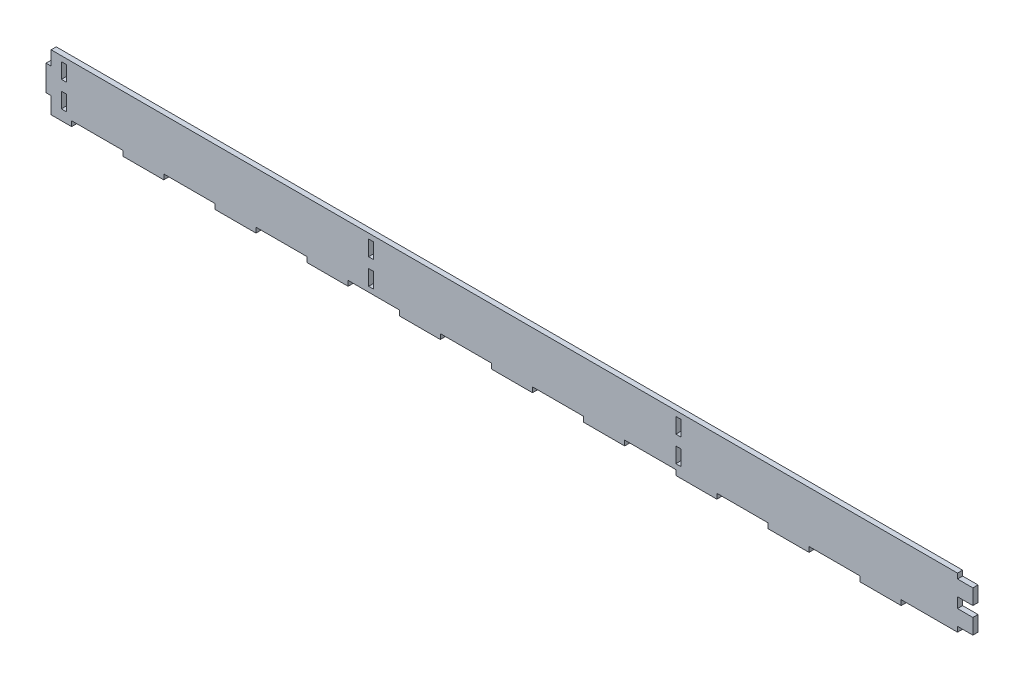
SolidWorks part; units mm, degrees
ref_plane "Front Plane" through (0, 0, 0) normal (0, 0, 1) x (1, 0, 0)
ref_plane "Top Plane" through (0, 0, 0) normal (0, 1, 0) x (1, 0, 0)
ref_plane "Right Plane" through (0, 0, 0) normal (1, 0, 0) x (0, 0, -1)
sketch "Sketch1" plane through (0, 0, 0) normal (0, 0, 1) x (1, 0, 0)
  line L0 (-15, 45) -> (-10, 45)
  line L1 (-885, 0) -> (-830, 0)
  line L2 (-885, 0) -> (-885, 5)
  line L3 (-885, 50) -> (885, 50)
  line L5 (-885, 5) -> (-900, 5)
  line L7 (-885, 20) -> (-900, 20)
  line L8 (-900, 5) -> (-900, 20)
  line L9 (-885, 45) -> (-900, 45)
  line L10 (-900, 30) -> (-900, 45)
  line L11 (-885, 30) -> (-900, 30)
  line L12 (-15, 30) -> (-15, 45)
  line L13 (-10, 30) -> (-15, 30)
  line L14 (-10, 45) -> (-10, 30)
  line L15 (-885, 20) -> (-885, 30)
  line L16 (-885, 45) -> (-885, 50)
  line L17 (0, 0) -> (0, -14.8696) construction
  line L18 (885, 30) -> (900, 30)
  line L19 (900, 30) -> (900, 45)
  line L20 (885, 45) -> (900, 45)
  line L21 (900, 5) -> (900, 20)
  line L22 (885, 20) -> (900, 20)
  line L23 (885, 5) -> (900, 5)
  line L24 (885, 5) -> (885, 0)
  line L25 (885, 20) -> (885, 30)
  line L26 (885, 45) -> (885, 50)
  line L27 (-15, 20) -> (-10, 20)
  line L29 (-830, 0) -> (-830, -5)
  line L30 (-830, -5) -> (-790, -5)
  line L31 (-790, 0) -> (-790, -5)
  line L32 (-700, 0) -> (-700, -5)
  line L33 (-740, -5) -> (-700, -5)
  line L34 (-740, 0) -> (-740, -5)
  line L35 (-610, 0) -> (-610, -5)
  line L36 (-650, -5) -> (-610, -5)
  line L37 (-650, 0) -> (-650, -5)
  line L38 (-520, 0) -> (-520, -5)
  line L39 (-560, -5) -> (-520, -5)
  line L40 (-560, 0) -> (-560, -5)
  line L41 (-430, 0) -> (-430, -5)
  line L42 (-470, -5) -> (-430, -5)
  line L43 (-470, 0) -> (-470, -5)
  line L44 (-340, 0) -> (-340, -5)
  line L45 (-380, -5) -> (-340, -5)
  line L46 (-380, 0) -> (-380, -5)
  line L47 (-250, 0) -> (-250, -5)
  line L48 (-290, -5) -> (-250, -5)
  line L49 (-290, 0) -> (-290, -5)
  line L50 (-160, 0) -> (-160, -5)
  line L51 (-200, -5) -> (-160, -5)
  line L52 (-200, 0) -> (-200, -5)
  line L53 (-70, 0) -> (-70, -5)
  line L54 (-110, -5) -> (-70, -5)
  line L55 (-110, 0) -> (-110, -5)
  line L56 (20, 0) -> (20, -5)
  line L57 (-20, -5) -> (20, -5)
  line L58 (-20, 0) -> (-20, -5)
  line L59 (110, 0) -> (110, -5)
  line L60 (70, -5) -> (110, -5)
  line L61 (70, 0) -> (70, -5)
  line L62 (200, 0) -> (200, -5)
  line L63 (160, -5) -> (200, -5)
  line L64 (160, 0) -> (160, -5)
  line L65 (290, 0) -> (290, -5)
  line L66 (250, -5) -> (290, -5)
  line L67 (250, 0) -> (250, -5)
  line L68 (380, 0) -> (380, -5)
  line L69 (340, -5) -> (380, -5)
  line L70 (340, 0) -> (340, -5)
  line L71 (470, 0) -> (470, -5)
  line L72 (430, -5) -> (470, -5)
  line L73 (430, 0) -> (430, -5)
  line L74 (560, 0) -> (560, -5)
  line L75 (520, -5) -> (560, -5)
  line L76 (520, 0) -> (520, -5)
  line L77 (650, 0) -> (650, -5)
  line L78 (610, -5) -> (650, -5)
  line L79 (610, 0) -> (610, -5)
  line L80 (740, 0) -> (740, -5)
  line L81 (700, -5) -> (740, -5)
  line L82 (700, 0) -> (700, -5)
  line L83 (830, 0) -> (830, -5)
  line L84 (790, -5) -> (830, -5)
  line L85 (790, 0) -> (790, -5)
  line L86 (-790, 0) -> (-740, 0)
  line L87 (-700, 0) -> (-650, 0)
  line L88 (-610, 0) -> (-560, 0)
  line L89 (-520, 0) -> (-470, 0)
  line L90 (-430, 0) -> (-380, 0)
  line L91 (-340, 0) -> (-290, 0)
  line L92 (-250, 0) -> (-200, 0)
  line L93 (-160, 0) -> (-110, 0)
  line L94 (-70, 0) -> (-20, 0)
  line L95 (20, 0) -> (70, 0)
  line L96 (110, 0) -> (160, 0)
  line L97 (200, 0) -> (250, 0)
  line L98 (290, 0) -> (340, 0)
  line L99 (380, 0) -> (430, 0)
  line L100 (470, 0) -> (520, 0)
  line L101 (560, 0) -> (610, 0)
  line L102 (650, 0) -> (700, 0)
  line L103 (740, 0) -> (790, 0)
  line L104 (830, 0) -> (885, 0)
  line L105 (-900, -5) -> (-900, 0) construction
  line L106 (-885, 0) -> (-885, 5) construction
  line L107 (-590, 20) -> (-590, 5) construction
  line L108 (-590, 5) -> (-585, 5) construction
  line L109 (-585, 5) -> (-585, 20) construction
  line L110 (-585, 20) -> (-590, 20) construction
  line L111 (-590, 45) -> (-590, 30) construction
  line L112 (-590, 30) -> (-585, 30) construction
  line L113 (-585, 30) -> (-585, 45) construction
  line L114 (-585, 45) -> (-590, 45) construction
  line L115 (-590, 20) -> (-590, 5)
  line L116 (-590, 5) -> (-585, 5)
  line L117 (-585, 5) -> (-585, 20)
  line L118 (-585, 20) -> (-590, 20)
  line L119 (-590, 45) -> (-590, 30)
  line L120 (-590, 30) -> (-585, 30)
  line L121 (-585, 30) -> (-585, 45)
  line L122 (-585, 45) -> (-590, 45)
  line L123 (610, 20) -> (610, 5) construction
  line L124 (610, 5) -> (615, 5) construction
  line L125 (615, 5) -> (615, 20) construction
  line L126 (615, 20) -> (610, 20) construction
  line L127 (610, 45) -> (610, 30) construction
  line L128 (610, 30) -> (615, 30) construction
  line L129 (615, 30) -> (615, 45) construction
  line L130 (615, 45) -> (610, 45) construction
  line L131 (310, 20) -> (310, 5) construction
  line L132 (310, 5) -> (315, 5) construction
  line L133 (315, 5) -> (315, 20) construction
  line L134 (315, 20) -> (310, 20) construction
  line L135 (310, 45) -> (310, 30) construction
  line L136 (310, 30) -> (315, 30) construction
  line L137 (315, 30) -> (315, 45) construction
  line L138 (315, 45) -> (310, 45) construction
  line L139 (10, 20) -> (10, 5) construction
  line L140 (10, 5) -> (15, 5) construction
  line L141 (15, 5) -> (15, 20) construction
  line L142 (15, 20) -> (10, 20) construction
  line L143 (10, 45) -> (10, 30) construction
  line L144 (10, 30) -> (15, 30) construction
  line L145 (15, 30) -> (15, 45) construction
  line L146 (15, 45) -> (10, 45) construction
  line L147 (-290, 20) -> (-290, 5) construction
  line L148 (-290, 5) -> (-285, 5) construction
  line L149 (-285, 5) -> (-285, 20) construction
  line L150 (-285, 20) -> (-290, 20) construction
  line L151 (-290, 45) -> (-290, 30) construction
  line L152 (-290, 30) -> (-285, 30) construction
  line L153 (-285, 30) -> (-285, 45) construction
  line L154 (-285, 45) -> (-290, 45) construction
  line L155 (610, 20) -> (610, 5)
  line L156 (610, 5) -> (615, 5)
  line L157 (615, 5) -> (615, 20)
  line L158 (615, 20) -> (610, 20)
  line L159 (610, 45) -> (610, 30)
  line L160 (610, 30) -> (615, 30)
  line L161 (615, 30) -> (615, 45)
  line L162 (615, 45) -> (610, 45)
  line L163 (310, 20) -> (310, 5)
  line L164 (310, 5) -> (315, 5)
  line L165 (315, 5) -> (315, 20)
  line L166 (315, 20) -> (310, 20)
  line L167 (310, 45) -> (310, 30)
  line L168 (310, 30) -> (315, 30)
  line L169 (315, 30) -> (315, 45)
  line L170 (315, 45) -> (310, 45)
  line L171 (10, 20) -> (10, 5)
  line L172 (10, 5) -> (15, 5)
  line L173 (15, 5) -> (15, 20)
  line L174 (15, 20) -> (10, 20)
  line L175 (10, 45) -> (10, 30)
  line L176 (10, 30) -> (15, 30)
  line L177 (15, 30) -> (15, 45)
  line L178 (15, 45) -> (10, 45)
  line L179 (-290, 20) -> (-290, 5)
  line L180 (-290, 5) -> (-285, 5)
  line L181 (-285, 5) -> (-285, 20)
  line L182 (-285, 20) -> (-290, 20)
  line L183 (-290, 45) -> (-290, 30)
  line L184 (-290, 30) -> (-285, 30)
  line L185 (-285, 30) -> (-285, 45)
  line L186 (-285, 45) -> (-290, 45)
  line L187 (-15, 5) -> (-15, 20)
  line L188 (-10, 5) -> (-15, 5)
  line L189 (-10, 20) -> (-10, 5)
  line L190 (0, 11.2098) -> (0, -5)
  line L191 (0, 36.2098) -> (-5, 36.2098)
  line L193 (0, 11.2098) -> (-5, 11.2098)
  line L194 (-5, 36.2098) -> (-5, 11.2098)
  line L195 (0, 23.7098) -> (-5, 11.2098) construction
  line L196 (0, 23.7098) -> (-5, 36.2098) construction
  line L197 (0, 36.2098) -> (0, 50)
  point P33 (0, -5)
  point P125 (0, 23.7098)
  dimension "D1" = 40
  dimension "D2" = 15
  dimension "D6" = 25
  dimension "D3" = 2
  dimension "D5" = 19
extrude "Boss-Extrude1" add sketch "Sketch1" against normal blind 5 contours L197 L191 L194 L193 L190 L57 L56 L95 L61 L60 L59 L96 L64 L63 L62 L97 L67 L66 L65 L98 L70 L69 L68 L99 L73 L72 L71 L100 L76 L75 L74 L101 L79 L78 L77 L102 L82 L81 L80 L103 L85 L84 L83 L104 L24 L23 L21 L22 L25 L18 L19
